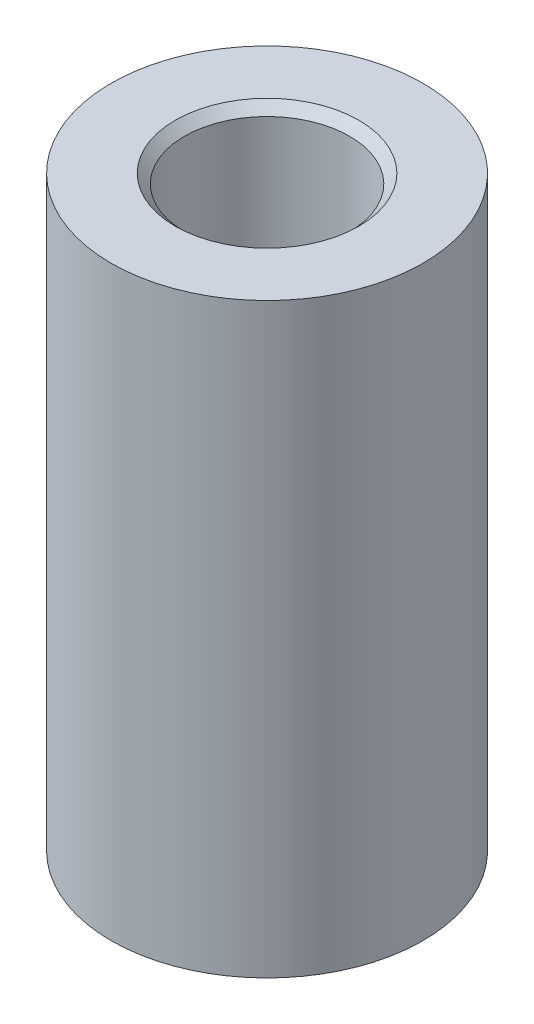
SolidWorks part; units mm, degrees
ref_plane "Front Plane" through (0, 0, 0) normal (0, 0, 1) x (1, 0, 0)
ref_plane "Top Plane" through (0, 0, 0) normal (0, 1, 0) x (1, 0, 0)
ref_plane "Right Plane" through (0, 0, 0) normal (1, 0, 0) x (0, 0, -1)
sketch "Sketch1" plane through (0, 0, 0) normal (0, 1, 0) x (1, 0, 0)
  circle A0 centre (-839.1446, 1451.4233) radius 3.575
  circle A1 centre (-839.1446, 1451.4233) radius 6.75
  dimension "D1" = 7.15
  dimension "D2" = 3.175
extrude "Boss-Extrude1" add sketch "Sketch1" along normal blind 25.4
chamfer "Chamfer1" distance 0.4 angle 45 2 edges at (-839.1446, 0, -1447.8483) (-839.1446, 25.4, -1447.8483)
